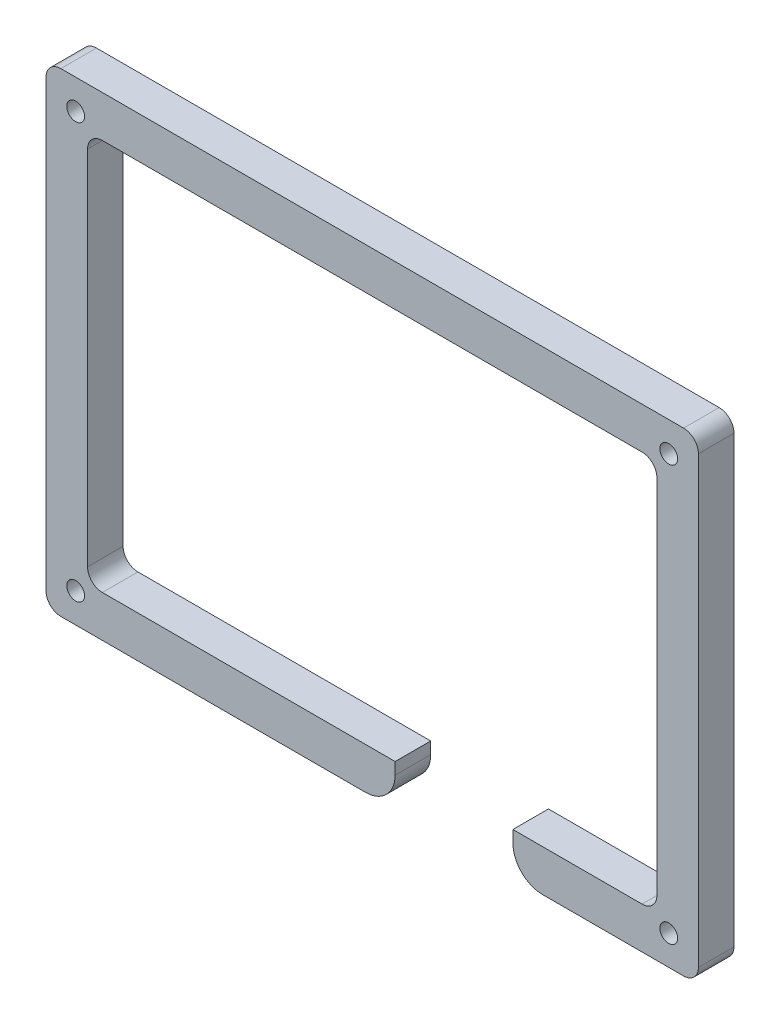
SolidWorks part; units mm, degrees
material "MDF"
ref_plane "Front Plane" through (0, 0, 0) normal (0, 0, 1) x (1, 0, 0)
ref_plane "Top Plane" through (0, 0, 0) normal (0, 1, 0) x (1, 0, 0)
ref_plane "Right Plane" through (0, 0, 0) normal (1, 0, 0) x (0, 0, -1)
sketch "Sketch2" plane through (0, 0, 0) normal (0, 0, 1) x (1, 0, 0)
  line L0 (-6.6646, 7) -> (-102.6646, 7)
  line L1 (0.3354, 80) -> (-109.6646, 80)
  line L2 (0.3354, 80) -> (0.3354, 0)
  line L3 (0.3354, 0) -> (-109.6646, 0)
  line L4 (-109.6646, 80) -> (-109.6646, 0)
  line L5 (-102.6646, 73) -> (-102.6646, 7)
  line L6 (-6.6646, 73) -> (-102.6646, 73)
  line L7 (-6.6646, 73) -> (-6.6646, 7)
  dimension "D1" = 7
  dimension "D2" = 110
extrude "Boss-Extrude2" add sketch "Sketch2" along normal blind 6
fillet "Fillet1" radius 2.5 4 edges at (-6.6646, 73, 3) (-102.6646, 73, 3) (-102.6646, 7, 3) (-6.6646, 7, 3)
sketch "Sketch3" plane through (0, 0, 6) normal (0, 0, 1) x (1, 0, 0)
  line L0 (0.3354, 80) -> (-109.6646, 80) construction
  line L1 (-109.6646, 80) -> (-109.6646, 0) construction
  line L2 (-109.6646, 0) -> (0.3354, 0) construction
  line L3 (0.3354, 0) -> (0.3354, 80) construction
  circle A0 centre (-4.6646, 75) radius 1.5
  circle A1 centre (-4.6646, 5) radius 1.5
  circle A2 centre (-104.6646, 5) radius 1.5
  circle A3 centre (-104.6646, 75) radius 1.5
  dimension "D1" = 5
  dimension "D2" = 5
  dimension "D3" = 5
  dimension "D4" = 5
  dimension "D5" = 5
  dimension "D6" = 5
  dimension "D7" = 5
  dimension "D8" = 5
extrude "Cut-Extrude1" cut sketch "Sketch3" against normal through all
fillet "Fillet2" radius 2.5 4 edges at (0.3354, 80, 3) (0.3354, 0, 3) (-109.6646, 0, 3) (-109.6646, 80, 3)
sketch "Sketch4" plane through (0, 0, 0) normal (0, 0, -1) x (-1, 0, 0)
  line L0 (30.9001, 0) -> (30.9498, 7)
  line L2 (107.1646, 0) -> (2.1646, 0) construction
  line L3 (100.1646, 7) -> (9.1646, 7) construction
  line L4 (30.9498, 7) -> (50.7991, 7)
  line L5 (50.7991, 7) -> (50.7991, 0)
  line L6 (-0.3354, 2.5) -> (-0.3354, 77.5) construction
  dimension "D1" = 31.2355
  dimension "D2" = 31.2851
  dimension "D3" = 51.1345
extrude "Cut-Extrude2" cut sketch "Sketch4" against normal through all and the other way through all flip side to cut
fillet "Fillet3" radius 5 2 edges at (-50.7991, 0, 3) (-30.9001, 0, 3)
